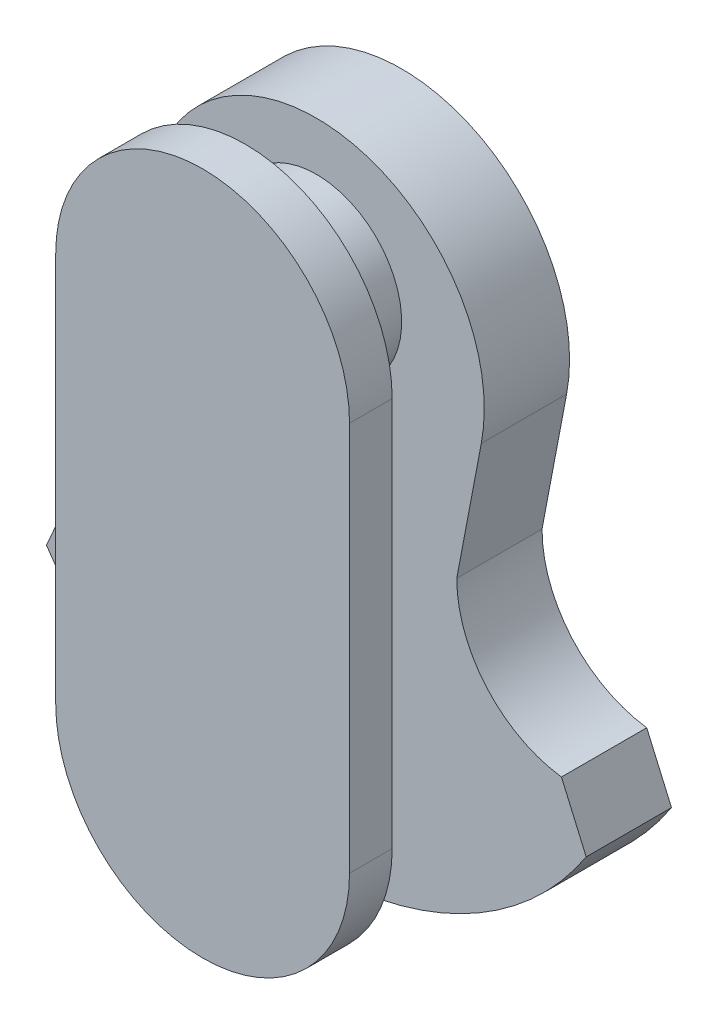
SolidWorks part; units mm, degrees
ref_plane "Спереди" through (0, 0, 0) normal (0, 0, 1) x (1, 0, 0)
ref_plane "Сверху" through (0, 0, 0) normal (0, 1, 0) x (1, 0, 0)
ref_plane "Справа" through (0, 0, 0) normal (1, 0, 0) x (0, 0, -1)
sketch "Эскиз1" plane through (0, 0, 0) normal (0, 0, 1) x (1, 0, 0)
  line L0 (-3411.2575, -878.8283) -> (-3294.3325, -883.0176) construction
  line L1 (513.7465, 159.1104) -> (518.9758, 171.093)
  line L2 (535.8855, 223.6162) -> (541.0696, 196.347)
  line L3 (570.6954, 271.1779) -> (570.6954, 265.6673)
  line L4 (605.5054, 223.6162) -> (600.3212, 196.347)
  line L5 (627.6443, 159.1104) -> (622.4151, 171.093)
  arc A0 (513.7465, 159.1104) -> (627.6443, 159.1104) centre (570.6954, 196.2698) ccw
  arc A1 (518.9758, 171.093) -> (541.0696, 196.347) centre (515.5896, 196.347) ccw
  arc A2 (622.4151, 171.093) -> (600.3212, 196.347) centre (625.8012, 196.347) cw
  arc A3 (535.8855, 223.6162) -> (605.5054, 223.6162) centre (570.6954, 230.2339) cw
  dimension "D2" = 68
  dimension "D3" = 13.074
  dimension "D4" = 25.48
  dimension "D5" = 70.8668
  dimension "D1" = 117
  dimension "D6" = 27.2691
extrude "Бобышка-Вытянуть1" add sketch "Эскиз1" along normal blind 18 contours L2 A1 L1 A0 L5 A2 L4 A3
sketch "Эскиз2" plane through (0, 0, 18) normal (0, 0, 1) x (1, 0, 0)
  line L0 (338.9833, 0) -> (729.9088, 0)
  circle A0 centre (570.6954, 237.3929) radius 18
extrude "Бобышка-Вытянуть2" add sketch "Эскиз2" along normal blind 15 separate body contours A0
sketch "Эскиз4" plane through (0, 0, 33) normal (0, 0, 1) x (1, 0, 0)
  line L3 (539.6954, 155.1468) -> (539.6954, 237.3929)
  line L4 (601.6954, 155.1468) -> (601.6954, 237.3929)
  arc A0 (539.6954, 237.3929) -> (601.6954, 237.3929) centre (570.6954, 237.3929) cw
  arc A1 (539.6954, 155.1468) -> (601.6954, 155.1468) centre (570.6954, 155.1468) ccw
  point P12 (601.6954, 196.2698)
extrude "Бобышка-Вытянуть3" add sketch "Эскиз4" along normal blind 9
combine bodies "Соединить3" operation type add bodies to combine 105 103 104
